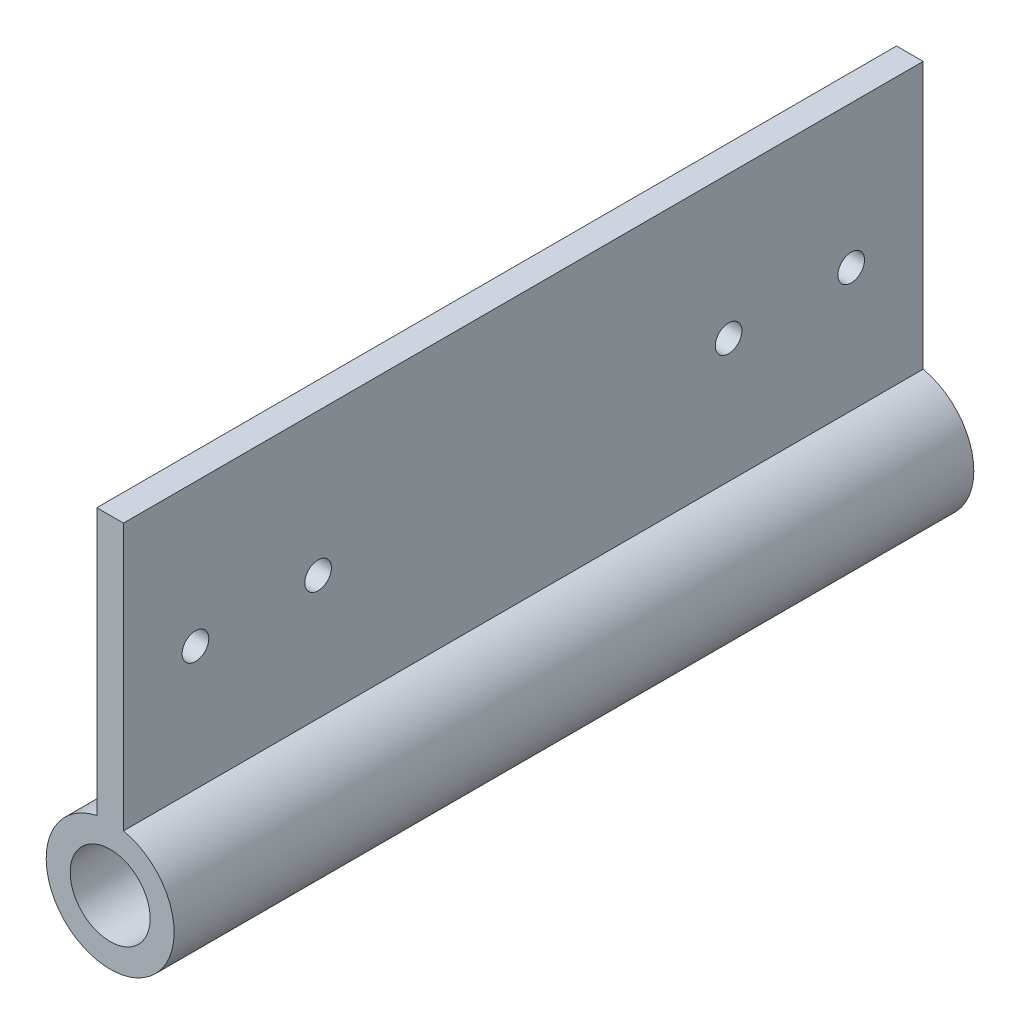
SolidWorks part; units mm, degrees
ref_plane "Front Plane" through (0, 0, 0) normal (0, 0, 1) x (1, 0, 0)
ref_plane "Top Plane" through (0, 0, 0) normal (0, 1, 0) x (1, 0, 0)
ref_plane "Right Plane" through (0, 0, 0) normal (1, 0, 0) x (0, 0, -1)
sketch "Sketch1" plane through (0, 0, 0) normal (0, 0, 1) x (1, 0, 0)
  line L0 (-2.5, 61.7367) -> (-2.5, 11.7367)
  line L1 (2.5, 61.7367) -> (2.5, 11.7367)
  line L2 (-2.5, 61.7367) -> (2.5, 61.7367)
  circle A0 centre (0, 0) radius 7.5
  arc A1 (-2.5, 11.7367) -> (2.5, 11.7367) centre (0, 0) ccw
  dimension "D1" = 15
  dimension "D2" = 12
  dimension "D3" = 5
  dimension "D4" = 50
extrude "Boss-Extrude1" add sketch "Sketch1" along normal blind 150
sketch "Sketch3" plane through (-2.5, 0, 0) normal (-1, 0, 0) x (0, 0, 1)
  line L0 (150, 11.7367) -> (150, 61.7367) construction
  line L6 (0, 11.7367) -> (0, 61.7367) construction
  circle A0 centre (113.5, 35) radius 2.5
  circle A1 centre (136.5, 35) radius 2.5
  circle A3 centre (36.5, 35) radius 2.5
  circle A4 centre (13.5, 35) radius 2.5
  point P4 (0, 0)
  point P5 (0, 0)
  point P8 (0, 0)
  point P9 (136.5, 35)
  dimension "D1" = 23
  dimension "D2" = 5
  dimension "D4" = 23
  dimension "D5" = 13.5
  dimension "D6" = 35
  dimension "D3" = 13.5
extrude "Cut-Extrude2" cut sketch "Sketch3" against normal through all
